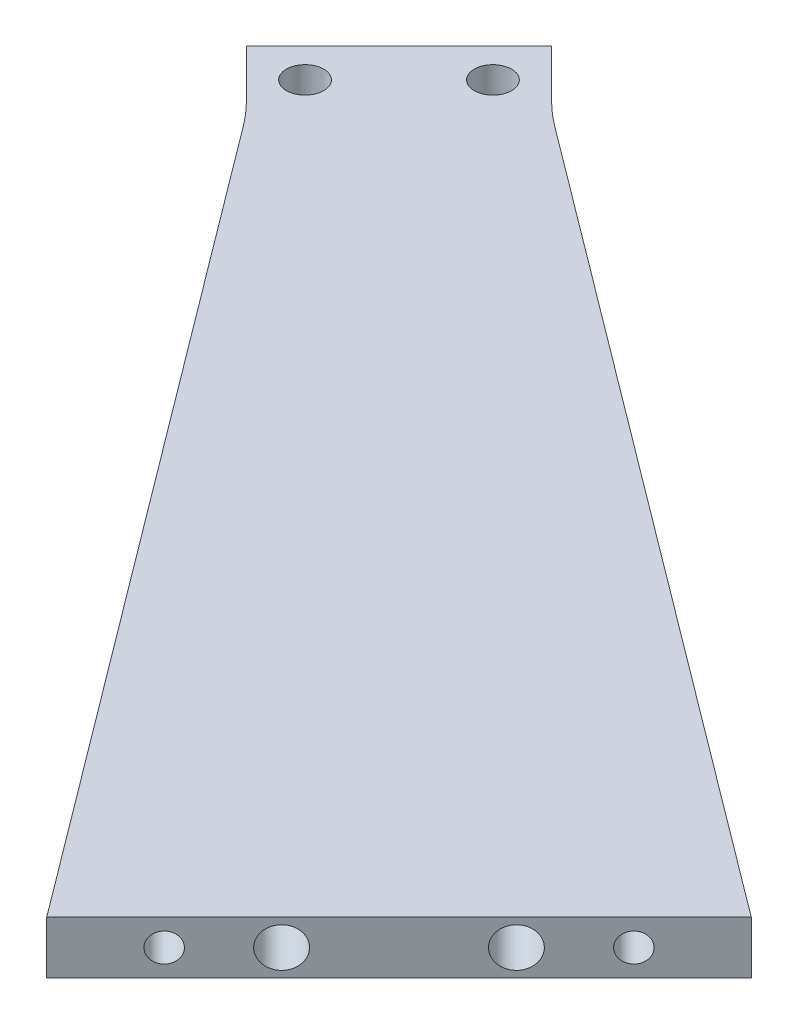
SolidWorks part; units mm, degrees
ref_plane "Front Plane" through (0, 0, 0) normal (0, 0, 1) x (1, 0, 0)
ref_plane "Top Plane" through (0, 0, 0) normal (0, 1, 0) x (1, 0, 0)
ref_plane "Right Plane" through (0, 0, 0) normal (1, 0, 0) x (0, 0, -1)
sketch "Sketch11" plane through (0, 0, 0) normal (0, -1, 0) x (1, 0, 0)
  line L5 (-8.4853, 9.8995) -> (-1.4237, 2.8379)
  line L6 (2.8379, -1.4237) -> (9.8995, -8.4853)
  line L7 (9.8995, -8.4853) -> (26.8701, 8.4853)
  line L8 (26.8701, 8.4853) -> (8.4853, 26.8701)
  line L9 (8.4853, 26.8701) -> (-8.4853, 9.8995)
  line L10 (-8.4853, 9.8995) -> (-1.4237, 2.8379)
  line L11 (2.8379, -1.4237) -> (9.8995, -8.4853)
  line L12 (9.8995, -8.4853) -> (26.8701, 8.4853)
  line L13 (26.8701, 8.4853) -> (8.4853, 26.8701)
  line L14 (8.4853, 26.8701) -> (-8.4853, 9.8995)
  arc A5 (2.8379, -1.4237) -> (-1.4237, 2.8379) centre (0, 0) ccw
  arc A10 (2.8379, -1.4237) -> (-1.4237, 2.8379) centre (0, 0) ccw
  circle A11 centre (19.799, 8.4853) radius 2.25
  circle A12 centre (19.799, 8.4853) radius 2.25
  circle A13 centre (8.4853, 19.799) radius 2.25
  circle A14 centre (8.4853, 19.799) radius 2.25
  dimension "D1" = 0
  dimension "D2" = 0
  dimension "D3" = 0
sketch "Sketch1" plane through (0, 0, 0) normal (0, 1, 0) x (1, 0, 0)
  line L0 (0, -99) -> (0, 99) construction
  line L1 (-99, 0) -> (99, 0) construction
  line L2 (-98.7155, -7.5) -> (98.7155, -7.5) construction
  line L3 (7.5, -98.7155) -> (7.5, 98.7155) construction
  line L4 (-98.7155, 7.5) -> (98.7155, 7.5) construction
  line L5 (-7.5, -98.7155) -> (-7.5, 98.7155) construction
  line L6 (-7.5, -99) -> (-7.5, 99) construction
  line L7 (7.5, -99) -> (7.5, 99) construction
  line L8 (-99, -7.5) -> (99, -7.5) construction
  line L9 (-99, 7.5) -> (99, 7.5) construction
  line L10 (-88.3883, -88.3883) -> (17.6777, -194.4544) construction
  line L11 (17.6777, -194.4544) -> (194.4544, -17.6777) construction
  line L12 (194.4544, -17.6777) -> (88.3883, 88.3883) construction
  line L13 (0, 0) -> (33755.9757, 33755.9757) construction
  line L14 (-88.3883, -88.3883) -> (-70.0036, -70.0036) construction
  line L15 (88.3883, 88.3883) -> (70.0036, 70.0036) construction
  line L16 (106.066, -106.066) -> (70.0036, -70.0036) construction
  line L17 (80.2566, -122.683) -> (8.4853, -26.8701)
  line L18 (8.4853, -26.8701) -> (1.4142, -19.799)
  line L19 (8.4853, -26.8701) -> (-8.4853, -9.8995) construction
  line L20 (1.4142, -19.799) -> (19.799, -1.4142)
  line L21 (9.8995, 8.4853) -> (26.8701, -8.4853) construction
  line L22 (19.799, -1.4142) -> (26.8701, -8.4853)
  line L23 (110.6622, -101.4698) -> (74.4487, -65.2563) construction
  line L24 (88.3883, 79.196) -> (74.4487, 65.2563) construction
  line L25 (185.262, -17.6777) -> (88.3883, 79.196) construction
  line L26 (17.6777, -185.262) -> (185.262, -17.6777) construction
  line L27 (-79.196, -88.3883) -> (17.6777, -185.262) construction
  line L28 (-79.196, -88.3883) -> (-65.2563, -74.4487) construction
  line L29 (26.8701, -8.4853) -> (122.683, -80.2566)
  line L30 (-79.196, -88.3883) -> (-65.4074, -74.5998) construction
  line L32 (88.3883, 79.196) -> (74.5998, 65.4074) construction
  line L34 (110.6622, -101.4698) -> (74.5998, -65.4074) construction
  line L35 (0, 0) -> (101.4698, -101.4698) construction
  line L38 (-14.9371, -14.9371) -> (7.0711, 7.0711) construction
  line L39 (80.2566, -122.683) -> (122.683, -80.2566)
  circle A0 centre (0, 0) radius 100 construction
  circle A1 centre (0, 0) radius 99 construction
  circle A2 centre (0, 0) radius 84 construction
  circle A5 centre (8.4853, -19.799) radius 2.25
  circle A6 centre (19.799, -8.4853) radius 2.25
  point P0 (101.4698, -101.4698)
  point P7 (0, 0)
  point P11 (0, 0)
  point P53 (62.7727, 34.4884)
  point P57 (0, 0)
  point P71 (74.0864, 45.8022)
  dimension "D1" = 200
  dimension "D2" = 1
  dimension "D3" = 15
  dimension "D6" = 25
  dimension "D7" = 25
  dimension "D8" = 50
  dimension "D11" = 4.5
  dimension "D9" = 7.5
  dimension "D10" = 45
  dimension "D15" = 60
  dimension "D12" = 143.5
  dimension "D13" = 10
  dimension "D4" = 7.5
  dimension "D5" = 7.5
extrude "Boss-Extrude1" add sketch "Sketch1" along normal mid plane 6.35
hole_wizard "#8-32 Tapped Hole1" positions "Sketch7" profile "Sketch8" tap size "#8-32" standard "ANSI Inch"
sketch "Sketch7" plane through (101.4698, 0, 101.4698) normal (0.7071, 0, 0.7071) x (0.7071, 0, -0.7071)
  point P0 (20, 0)
  point P2 (-20, 0)
  point P10 (0, 0)
  point P15 (-9.3161, -3.175)
  point P18 (0, 0)
  dimension "D1" = 20
  dimension "D2" = 20
sketch "Sketch8" plane through (115.612, 0, 87.3277) normal (0, 1, 0) x (0.7071, 0, -0.7071)
  line L0 (0, 0) -> (0, 11.7478)
  line L1 (0, 11.7478) -> (1.7272, 10.71)
  line L2 (1.7272, 10.71) -> (1.7272, 0)
  line L5 (1.7272, 0) -> (0, 0)
  line L10 (0, 11.7478) -> (-1.7272, 10.71) construction
  line L11 (0, -6.35) -> (0, 107.95) construction
  dimension "Tap Drill Dia." = 3.4544
  dimension "Tap Drill Depth" = 10.71
  dimension "Drill Angle" = 118
cosmetic thread "Hole Thread1" parameters "D1"=8.33, "D2"=4.1656
cosmetic thread "Hole Thread2" parameters "D1"=8.33, "D2"=4.1656
hole_wizard "3/16 (0.1875) Dowel Hole1" positions "Sketch9" profile "Sketch10" hole size "3/16" standard "ANSI Inch"
sketch "Sketch9" plane through (101.4698, 0, 101.4698) normal (0.7071, 0, 0.7071) x (0.7071, 0, -0.7071)
  point P0 (-10, 0)
  point P2 (10, 0)
  point P13 (0.2684, -0.7264)
  dimension "D1" = 10
  dimension "D2" = 10
sketch "Sketch10" plane through (94.3988, 0, 108.5409) normal (0, 1, 0) x (0.7071, 0, -0.7071)
  line L0 (0, 0) -> (0, 14.2608)
  line L1 (0, 14.2608) -> (2.3812, 12.83)
  line L2 (2.3812, 12.83) -> (2.3812, 0)
  line L5 (2.3812, 0) -> (0, 0)
  line L10 (0, 14.2608) -> (-2.3813, 12.83) construction
  line L11 (0, -6.35) -> (0, 107.95) construction
  dimension "Hole Dia." = 4.7625
  dimension "Hole Depth" = 12.83
  dimension "Drill Angle" = 118
fillet "Fillet1" radius 25 2 edges at (26.8701, 0, 8.4853) (8.4853, 0, 26.8701)
